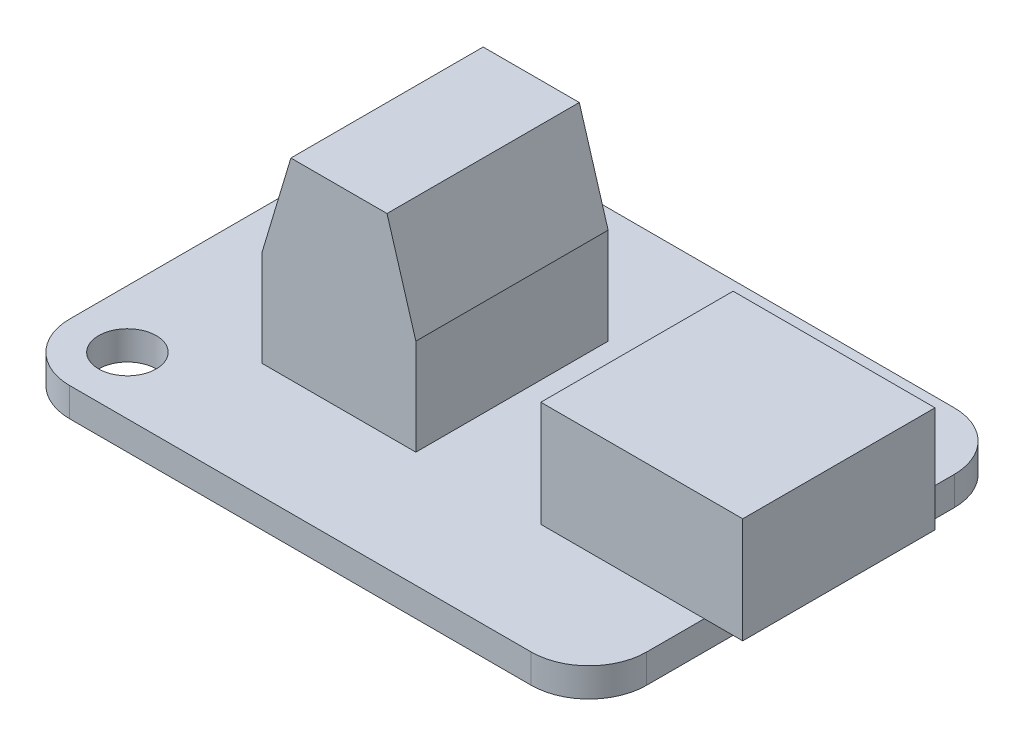
SolidWorks part; units mm, degrees
ref_plane "Спереди" through (0, 0, 0) normal (0, 0, 1) x (1, 0, 0)
ref_plane "Сверху" through (0, 0, 0) normal (0, 1, 0) x (1, 0, 0)
ref_plane "Справа" through (0, 0, 0) normal (1, 0, 0) x (0, 0, -1)
sketch "Эскиз1" plane through (0, 0, 0) normal (0, 1, 0) x (1, 0, 0)
  line L0 (-28.1983, 2.8346) -> (-28.1983, -13.1654)
  line L1 (-25.1983, 5.8346) -> (-1.1983, 5.8346)
  line L2 (1.8017, 2.8346) -> (1.8017, -13.1654)
  line L3 (-1.1983, -16.1654) -> (-25.1983, -16.1654)
  arc A0 (1.8017, -13.1654) -> (-1.1983, -16.1654) centre (-1.1983, -13.1654) cw
  arc A1 (-25.1983, -16.1654) -> (-28.1983, -13.1654) centre (-25.1983, -13.1654) cw
  arc A2 (-25.1983, 5.8346) -> (-28.1983, 2.8346) centre (-25.1983, 2.8346) ccw
  arc A3 (1.8017, 2.8346) -> (-1.1983, 5.8346) centre (-1.1983, 2.8346) ccw
  circle A4 centre (-25.1983, -13.1654) radius 1.5
  circle A5 centre (-25.1983, 2.8346) radius 1.5
  point P8 (-28.1983, -16.1654)
  point P11 (-28.1983, 5.8346)
  point P14 (1.8017, 5.8346)
  dimension "D3" = 3
  dimension "D1" = 22
  dimension "D2" = 30
extrude "Бобышка-Вытянуть1" add sketch "Эскиз1" along normal blind 1.5
sketch "Эскиз2" plane through (0, 1.5, 0) normal (0, 1, 0) x (1, 0, 0)
  line L0 (1.8017, -5.1654) -> (-6.6983, -5.1654) construction
  line L2 (1.8017, -13.1654) -> (1.8017, 2.8346) construction
  line L3 (1.8017, -0.1654) -> (-6.6983, -0.1654)
  line L4 (1.8017, -10.1654) -> (-6.6983, -10.1654)
  line L5 (-6.6983, -0.1654) -> (-6.6983, -10.1654)
  line L6 (1.8017, -10.1654) -> (3.8017, -10.1654)
  line L7 (3.8017, -10.1654) -> (3.8017, -0.1654)
  line L8 (3.8017, -0.1654) -> (1.8017, -0.1654)
  dimension "D1" = 5
  dimension "D2" = 5
extrude "Бобышка-Вытянуть2" add sketch "Эскиз2" along normal blind 5.5
sketch "Эскиз3" plane through (0, 1.5, 0) normal (0, 1, 0) x (1, 0, 0)
  line L0 (-28.1983, -5.1654) -> (-13.1983, -5.1654) construction
  line L1 (-28.1983, 2.8346) -> (-28.1983, -13.1654) construction
  line L4 (-13.1983, -10.1654) -> (-13.1983, -0.1654)
  line L5 (-13.1983, -0.1654) -> (-21.1983, -0.1654)
  line L6 (-21.1983, -0.1654) -> (-21.1983, -10.1654)
  line L7 (-21.1983, -10.1654) -> (-13.1983, -10.1654)
  dimension "D1" = 5
  dimension "D2" = 5
  dimension "D3" = 7
  dimension "D4" = 8
extrude "Бобышка-Вытянуть3" add sketch "Эскиз3" along normal blind 5
sketch "Эскиз4" plane through (0, 0, 10.1654) normal (0, 0, 1) x (1, 0, 0)
  line L0 (-17.1983, 6.5) -> (-17.1983, 11.5) construction
  line L1 (-21.1983, 6.5) -> (-13.1983, 6.5) construction
  line L2 (-17.1983, 11.5) -> (-19.6983, 11.5)
  line L3 (-19.6983, 11.5) -> (-14.6983, 11.5)
  line L4 (-14.6983, 11.5) -> (-13.1983, 6.5)
  line L5 (-19.6983, 11.5) -> (-21.1983, 6.5)
  line L6 (-21.1983, 6.5) -> (-13.1983, 6.5)
  line M3 (-13.1983, 6.5) -> (-21.1983, 6.5)
extrude "Бобышка-Вытянуть4" add sketch "Эскиз4" against normal up to vertex (10 mm away) contours L6 L0 L2 L5 | L0 L4 L3 M3 up to point (-13.1983, 6.5, 0.1654)
